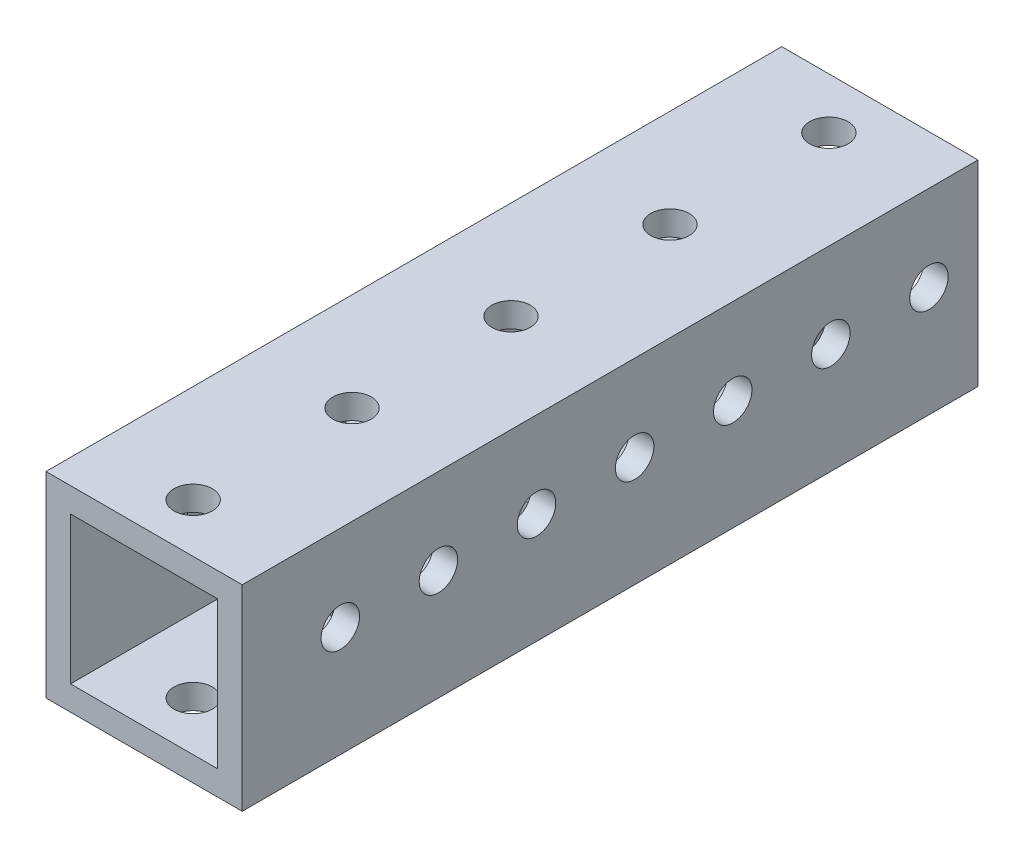
SolidWorks part; units mm, degrees
ref_plane "Front Plane" through (0, 0, 0) normal (0, 0, 1) x (1, 0, 0)
ref_plane "Top Plane" through (0, 0, 0) normal (0, 1, 0) x (1, 0, 0)
ref_plane "Right Plane" through (0, 0, 0) normal (1, 0, 0) x (0, 0, -1)
sketch "Sketch1" plane through (0, 0, 0) normal (0, 0, 1) x (1, 0, 0)
  line L0 (3.175, 22.225) -> (22.225, 22.225)
  line L1 (0, 0) -> (25.4, 0)
  line L2 (0, 0) -> (0, 25.4)
  line L3 (0, 25.4) -> (25.4, 25.4)
  line L4 (25.4, 0) -> (25.4, 25.4)
  line L5 (22.225, 3.175) -> (22.225, 22.225)
  line L6 (3.175, 3.175) -> (22.225, 3.175)
  line L7 (3.175, 3.175) -> (3.175, 22.225)
  dimension "D1" = 25.4
  dimension "D2" = 25.4
  dimension "D3" = 3.175
extrude "Boss-Extrude1" add sketch "Sketch1" along normal blind 95.25
sketch "Sketch2" plane through (0, 0, 0) normal (-1, 0, 0) x (0, 0, 1)
  line L0 (95.25, 25.4) -> (95.25, 0) construction
  line L2 (95.25, 0) -> (0, 0) construction
  circle A0 centre (82.55, 14.2875) radius 2.4892
  circle A1 centre (69.85, 14.2875) radius 2.4892
  circle A2 centre (57.15, 14.2875) radius 2.4892
  circle A3 centre (44.45, 14.2875) radius 2.4892
  circle A4 centre (31.75, 14.2875) radius 2.4892
  circle A5 centre (19.05, 14.2875) radius 2.4892
  circle A6 centre (6.35, 14.2875) radius 2.4892
  dimension "D1" = 12.7
  dimension "D2" = 4.9784
  dimension "D3" = 14.2875
  dimension "D5" = 12.7
  dimension "D4" = 7
extrude "Cut-Extrude1" cut sketch "Sketch2" against normal blind 95.25
sketch "Sketch5" plane through (0, 0, 0) normal (0, -1, 0) x (-1, 0, 0)
  line L0 (0, -95.25) -> (-25.4, -95.25) construction
  line L1 (-12.7, -88.9) -> (-12.7, -68.326) construction
  line L2 (0, -95.25) -> (0, 0) construction
  circle A0 centre (-12.7, -88.9) radius 2.4892
  circle A1 centre (-12.7, -68.326) radius 2.4892
  circle A2 centre (-12.7, -47.752) radius 2.4892
  circle A3 centre (-12.7, -27.178) radius 2.4892
  circle A4 centre (-12.7, -6.604) radius 2.4892
  dimension "D1" = 6.35
  dimension "D2" = 12.7
  dimension "D3" = 4.9784
  dimension "D5" = 20.574
  dimension "D4" = 5
extrude "Cut-Extrude3" cut sketch "Sketch5" against normal blind 95.25
